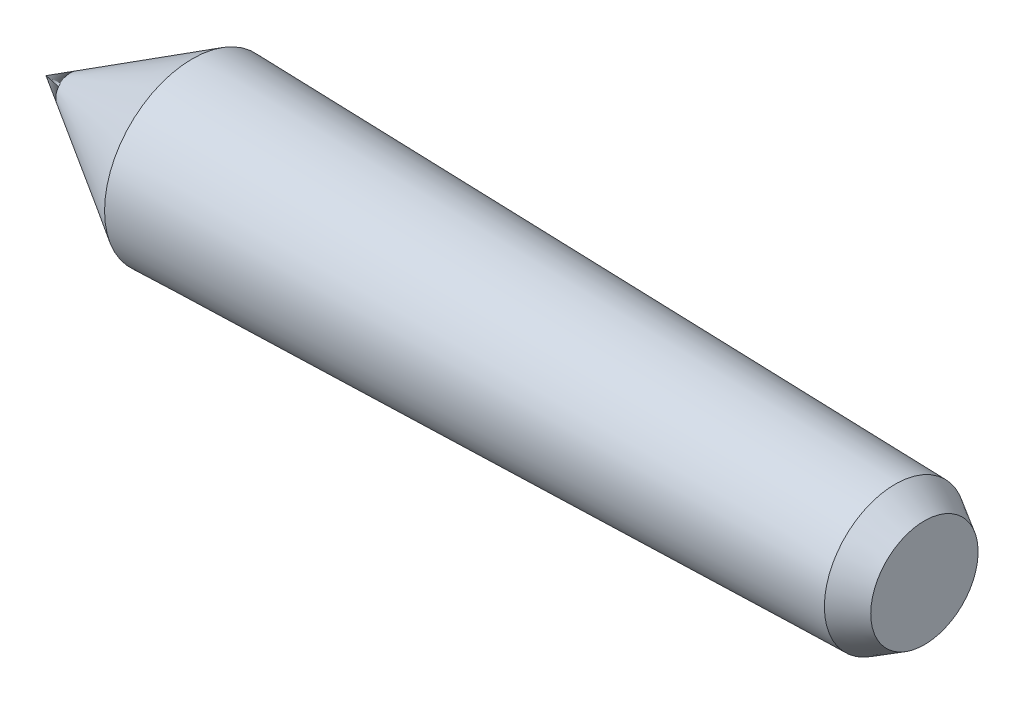
SolidWorks part; units mm, degrees
ref_plane "Front Plane" through (0, 0, 0) normal (0, 0, 1) x (1, 0, 0)
ref_plane "Top Plane" through (0, 0, 0) normal (0, 1, 0) x (1, 0, 0)
ref_plane "Right Plane" through (0, 0, 0) normal (1, 0, 0) x (0, 0, -1)
sketch "Sketch1" plane through (0, 0, 0) normal (0, 0, 1) x (1, 0, 0)
  line L0 (0, 0) -> (90, 0)
  line L1 (90, 0) -> (90, 5.5)
  line L2 (90, 5.5) -> (87, 7.25)
  line L3 (87, 7.25) -> (15, 9)
  line L4 (15, 9) -> (0, 0)
  dimension "D1" = 90
  dimension "D2" = 5.5
  dimension "D3" = 3
  dimension "D4" = 7.25
  dimension "D5" = 9
  dimension "D6" = 15
revolve "Revolve1" add sketch "Sketch1" angle 360 about L0
